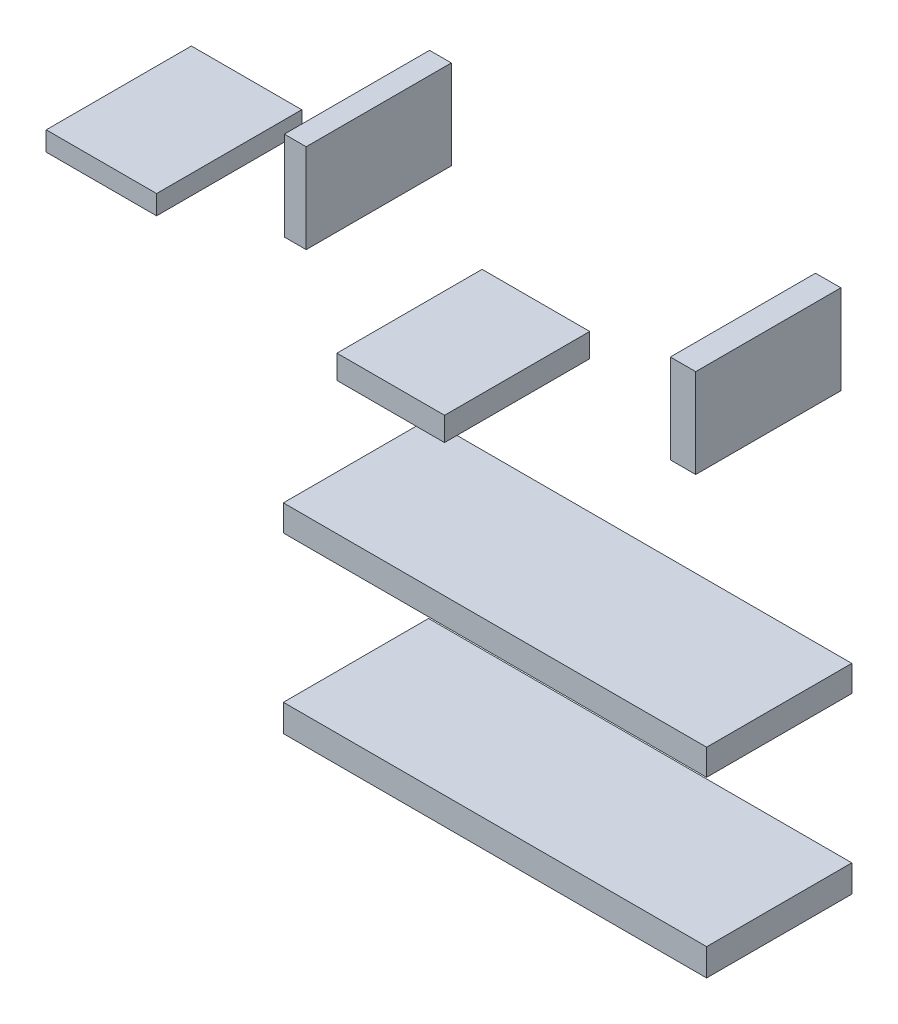
SolidWorks part; units mm, degrees
ref_plane "Ön Düzlem" through (0, 0, 0) normal (0, 0, 1) x (1, 0, 0)
ref_plane "Üst Düzlem" through (0, 0, 0) normal (0, 1, 0) x (1, 0, 0)
ref_plane "Sağ Düzlem" through (0, 0, 0) normal (1, 0, 0) x (0, 0, -1)
sketch "Çizim1" plane through (0, 0, 0) normal (0, 0, 1) x (1, 0, 0)
  line L0 (-8.7555, -33.4) -> (34.9445, -33.4) construction
  line L1 (-0.9609, -1.4924) -> (8.6761, -1.4924)
  line L2 (-0.9609, -1.4924) -> (-0.9609, -3.6112)
  line L3 (-0.9609, -3.6112) -> (8.6761, -3.6112)
  line L4 (8.6761, -1.4924) -> (8.6761, -3.6112)
  line L5 (-26.995, 2.8096) -> (-17.1115, 2.8096)
  line L6 (-26.995, 2.8096) -> (-26.995, 1.0768)
  line L7 (-26.995, 1.0768) -> (-17.1115, 1.0768)
  line L8 (-17.1115, 2.8096) -> (-17.1115, 1.0768)
  line L9 (-5.6693, 13.1375) -> (-3.7154, 13.1375)
  line L10 (-5.6693, 13.1375) -> (-5.6693, 5.1543)
  line L11 (-5.6693, 5.1543) -> (-3.7154, 5.1543)
  line L12 (-3.7154, 13.1375) -> (-3.7154, 5.1543)
  line L13 (-5.7555, -15.5) -> (32.1445, -15.5)
  line L14 (28.8973, 13.1375) -> (31.1666, 13.1375)
  line L15 (28.8973, 13.1375) -> (28.8973, 5.1543)
  line L16 (28.8973, 5.1543) -> (31.1666, 5.1543)
  line L17 (31.1666, 13.1375) -> (31.1666, 5.1543)
  line L18 (-5.7555, -15.5) -> (-5.7555, -17.84)
  line L19 (-5.7555, -17.84) -> (32.1445, -17.84)
  line L20 (32.1445, -15.5) -> (32.1445, -17.84)
  line L21 (-5.7555, -30.9664) -> (32.1445, -30.9664)
  line L22 (-5.7555, -30.9664) -> (-5.7555, -33.4)
  line L23 (-5.7555, -33.4) -> (32.1445, -33.4)
  line L24 (32.1445, -30.9664) -> (32.1445, -33.4)
extrude "Yükseklik-Ekstrüzyon1" add sketch "Çizim1" against normal blind 13
